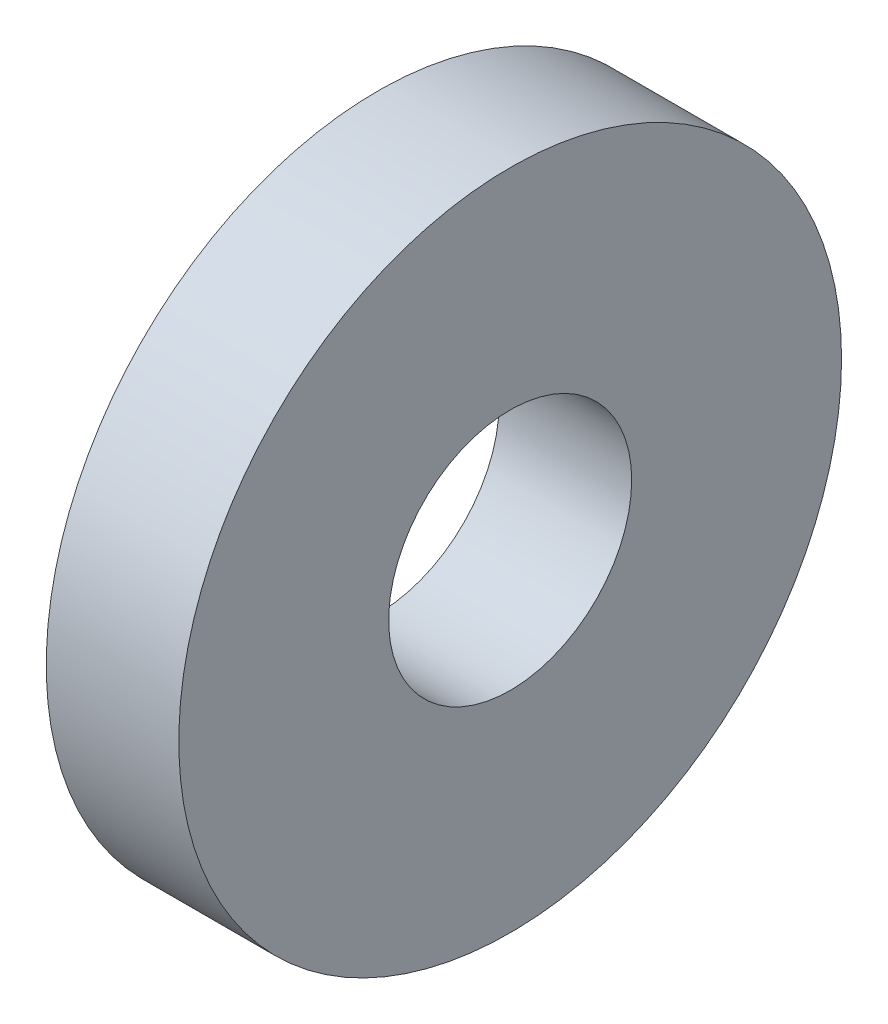
SolidWorks part; units mm, degrees
ref_plane "前视基准面" through (0, 0, 0) normal (0, 0, 1) x (1, 0, 0)
ref_plane "上视基准面" through (0, 0, 0) normal (0, 1, 0) x (1, 0, 0)
ref_plane "右视基准面" through (0, 0, 0) normal (1, 0, 0) x (0, 0, -1)
sketch "草图1" plane through (0, 0, 0) normal (1, 0, 0) x (0, 0, -1)
  circle A0 centre (0, 0) radius 7.5
  circle A1 centre (0, 0) radius 2.75
  dimension "D1" = 15
  dimension "D2" = 5.5
extrude "凸台-拉伸1" add sketch "草图1" along normal blind 3
